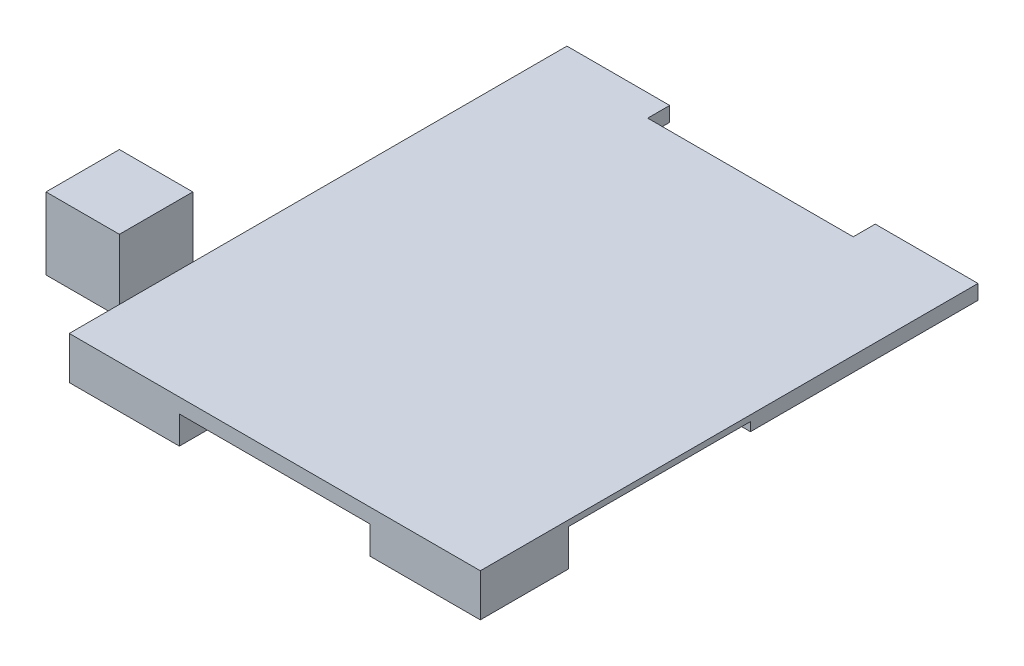
SolidWorks part; units mm, degrees
ref_plane "Front Plane" through (0, 0, 0) normal (0, 0, 1) x (1, 0, 0)
ref_plane "Top Plane" through (0, 0, 0) normal (0, 1, 0) x (1, 0, 0)
ref_plane "Right Plane" through (0, 0, 0) normal (1, 0, 0) x (0, 0, -1)
sketch "Sketch1" plane through (0, 0, 0) normal (0, 1, 0) x (1, 0, 0)
  line L17 (-4.8877, -8.1462) -> (-4.8877, -8.2)
  line L18 (-14, -8.2) -> (-4.8877, -8.2)
  line L19 (-14, -8.2) -> (-14, -10.2)
  line L20 (-14, -10.2) -> (14, -10.2)
  line L21 (14, -8.2) -> (14, -10.2)
  line L22 (4.8877, -8.1462) -> (4.8877, -8.2)
  line L23 (4.8877, -8.2) -> (14, -8.2)
  line L24 (0, 0) -> (17.0476, 0) construction
  line L25 (4.8877, 8.2) -> (14, 8.2)
  line L26 (4.8877, 8.1462) -> (4.8877, 8.2)
  line L27 (14, 8.2) -> (14, 11.2)
  line L29 (-14, 8.2) -> (-14, 11.2084)
  line L30 (-14, 8.2) -> (-4.8877, 8.2)
  line L31 (-4.8877, 8.1462) -> (-4.8877, 8.2)
  line L32 (7, 23.7) -> (14, 23.7)
  line L34 (-14, 11.2084) -> (-14, 23.2084)
  line L36 (14, 11.2) -> (14, 21.7)
  line L37 (-14, 23.7) -> (-7, 23.7)
  line L38 (-14, 23.7) -> (-14, 23.2084)
  line L40 (14, 23.7) -> (14, 21.7)
  line L41 (0, 0) -> (0, -7.2922) construction
  line L43 (-7, 23.7) -> (-7, 22.2)
  line L44 (-7, 22.2) -> (7, 22.2)
  line L45 (7, 23.7) -> (7, 22.2)
  line L50 (9.1652, -2.5) -> (7, -2.5)
  line L51 (7, 2.5) -> (7, -2.5)
  line L52 (9.1652, 2.5) -> (7, 2.5)
  arc A1 (4.8877, -8.1462) -> (9.1652, -2.5) centre (0, 0) ccw
  arc A3 (-4.8877, 8.1462) -> (-4.8877, -8.1462) centre (0, 0) ccw
  arc A4 (9.1652, 2.5) -> (4.8877, 8.1462) centre (0, 0) ccw
  point P9 (0, -10.2)
  dimension "D1" = 19
  dimension "D6" = 2
  dimension "D2" = 8.2
  dimension "D3" = 28
  dimension "D4" = 0
  dimension "D5" = 2
  dimension "D7" = 15.5
  dimension "D8" = 8.2
  dimension "D9" = 8.2
  dimension "D10" = 14
  dimension "D11" = 7
  dimension "D12" = 1.5
extrude "Boss-Extrude1" add sketch "Sketch1" against normal blind 0.6
sketch "Sketch3" plane through (0, 0, 0) normal (0, 1, 0) x (1, 0, 0)
  line L1 (-23.1401, 2.3559) -> (-18.1401, 2.3559)
  line L2 (-23.1401, 2.3559) -> (-23.1401, -2.6441)
  line L3 (-23.1401, -2.6441) -> (-18.1401, -2.6441)
  line L4 (-18.1401, 2.3559) -> (-18.1401, -2.6441)
  dimension "D1" = 5
  dimension "D2" = 5
extrude "Boss-Extrude3" add sketch "Sketch3" against normal blind 4.5 and the other way blind 0.4 separate body
sketch "Sketch4" plane through (0, 0, 0) normal (0, 1, 0) x (1, 0, 0)
  line L0 (14, 8.2) -> (14, 23.7) construction
  line L1 (-14, 23.7) -> (-7, 23.7)
  line L2 (-14, 23.7) -> (-14, 22.2)
  line L4 (-7, 23.7) -> (-7, 22.2)
  line L5 (7, 23.7) -> (14, 23.7)
  line L6 (7, 23.7) -> (7, 22.2)
  line L8 (14, 23.7) -> (14, 22.2)
  line L9 (-14, -10.2) -> (14, -10.2) construction
  line L10 (-7, 22.2) -> (7, 22.2)
  line L11 (-14, 22.2) -> (-14, -10.2)
  line L12 (-14, -10.2) -> (14, -10.2)
  line L13 (14, 22.2) -> (14, -10.2)
extrude "Boss-Extrude5" add sketch "Sketch4" along normal blind 0.4
sketch "Sketch5" plane through (0, 0, 0) normal (0, 1, 0) x (1, 0, 0)
  line L0 (0, 0) -> (0, -10.6838) construction
  line L5 (-11, -8.2) -> (-11, -4.2)
  line L6 (-14, -4.2) -> (-11, -4.2)
  line L7 (-14, -10.2) -> (-14, -4.2)
  line L8 (-14, -10.2) -> (-9.8877, -10.2)
  line L9 (-6.5, -8.2) -> (-6.5, -10.2)
  line L17 (-14, -10.2) -> (14, -10.2) construction
  line L18 (-11, -8.2) -> (-6.5, -8.2)
  line L19 (-9.8877, -10.2) -> (-6.5, -10.2)
  line L20 (9.8877, -10.2) -> (6.5, -10.2)
  line L21 (11, -8.2) -> (6.5, -8.2)
  line L22 (6.5, -8.2) -> (6.5, -10.2)
  line L23 (14, -10.2) -> (9.8877, -10.2)
  line L24 (14, -10.2) -> (14, -4.2)
  line L25 (14, -4.2) -> (11, -4.2)
  line L26 (11, -8.2) -> (11, -4.2)
  dimension "D1" = 6.5
  dimension "D2" = 2
  dimension "D3" = 11
  dimension "D4" = 4
extrude "Boss-Extrude6" add sketch "Sketch5" against normal blind 2.5
